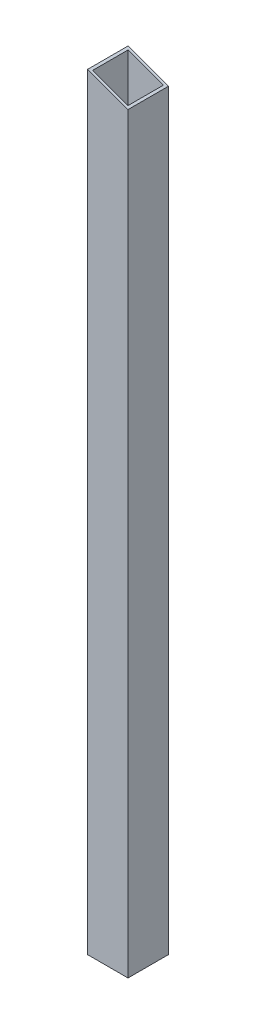
SolidWorks part; units mm, degrees
ref_plane "Front Plane" through (0, 0, 0) normal (0, 0, 1) x (1, 0, 0)
ref_plane "Top Plane" through (0, 0, 0) normal (0, 1, 0) x (1, 0, 0)
ref_plane "Right Plane" through (0, 0, 0) normal (1, 0, 0) x (0, 0, -1)
sketch "Sketch1" plane through (0, 0, 0) normal (0, 1, 0) x (1, 0, 0)
  line L1 (-12.7, -12.7) -> (12.7, -12.7)
  line L2 (-12.7, -12.7) -> (-12.7, 12.7)
  line L3 (-12.7, 12.7) -> (12.7, 12.7)
  line L4 (12.7, -12.7) -> (12.7, 12.7)
  line L5 (-12.7, -12.7) -> (12.7, 12.7) construction
  line L6 (-12.7, 12.7) -> (12.7, -12.7) construction
  line L7 (-11.1125, -11.1125) -> (11.1125, -11.1125)
  line L8 (-11.1125, -11.1125) -> (-11.1125, 11.1125)
  line L9 (-11.1125, 11.1125) -> (11.1125, 11.1125)
  line L10 (11.1125, -11.1125) -> (11.1125, 11.1125)
  line L11 (-11.1125, -11.1125) -> (11.1125, 11.1125) construction
  line L12 (-11.1125, 11.1125) -> (11.1125, -11.1125) construction
  point P0 (0, 0)
  point P6 (0, 0)
  dimension "D1" = 25.4
  dimension "D2" = 25.4
  dimension "D3" = 1.5875
  dimension "D4" = 1.5875
extrude "Boss-Extrude1" add sketch "Sketch1" along normal blind 482.6
sketch "Sketch2" plane through (0, 0, 12.7) normal (0, 0, 1) x (1, 0, 0)
  line L0 (-12.7, 482.6) -> (12.7, 473.3552)
  line L1 (12.7, 482.6) -> (12.7, 0) construction
  line L2 (12.7, 473.3552) -> (12.7, 482.6)
  line L3 (12.7, 482.6) -> (-12.7, 482.6)
  dimension "D1" = 20
extrude "Cut-Extrude1" cut sketch "Sketch2" against normal blind 25.4
